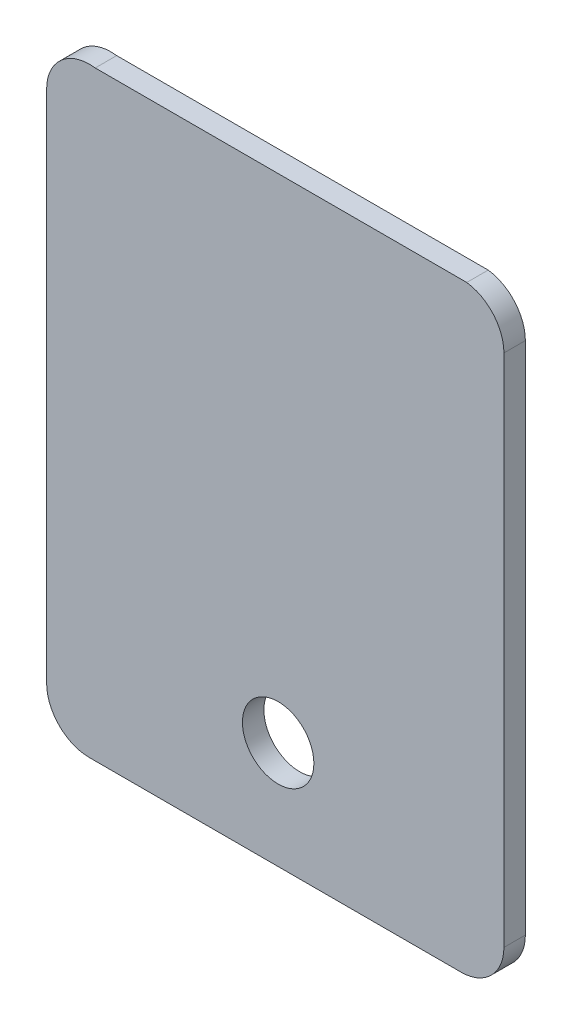
SolidWorks part; units mm, degrees
ref_plane "Спереди" through (0, 0, 0) normal (0, 0, 1) x (1, 0, 0)
ref_plane "Сверху" through (0, 0, 0) normal (0, 1, 0) x (1, 0, 0)
ref_plane "Справа" through (0, 0, 0) normal (1, 0, 0) x (0, 0, -1)
sketch "Эскиз1" plane through (0, 0, 0) normal (0, 0, 1) x (1, 0, 0)
  line L2 (-160.5469, 6.8677) -> (-134.5469, 6.8677)
  line L4 (-160.1469, 48.8677) -> (-134.1469, 48.8677)
  line L5 (-163.5469, 9.8677) -> (-163.5469, 45.8944)
  line L6 (-131.5469, 9.8677) -> (-131.5469, 45.8944)
  arc A0 (-160.1469, 48.8677) -> (-163.5469, 45.8944) centre (-160.5469, 45.8944) ccw
  arc A1 (-134.1469, 48.8677) -> (-131.5469, 45.8944) centre (-134.5469, 45.8944) cw
  arc A2 (-134.5469, 6.8677) -> (-131.5469, 9.8677) centre (-134.5469, 9.8677) ccw
  arc A3 (-160.5469, 6.8677) -> (-163.5469, 9.8677) centre (-160.5469, 9.8677) cw
  dimension "D1" = 3
  dimension "D2" = 42
  dimension "D3" = 32
extrude "Бобышка-Вытянуть1" add sketch "Эскиз1" along normal blind 1.5
sketch "Эскиз2" plane through (0, 0, 1.5) normal (0, 0, 1) x (1, 0, 0)
  line L0 (-147.3469, 4.5391) -> (-147.3469, 21.7458) construction
  line L1 (-160.5469, 6.8677) -> (-134.5469, 6.8677) construction
  circle A0 centre (-147.3469, 14.3677) radius 2.5
  dimension "D1" = 5
  dimension "D2" = 7.5
extrude "Вырез-Вытянуть1" cut sketch "Эскиз2" against normal through all
